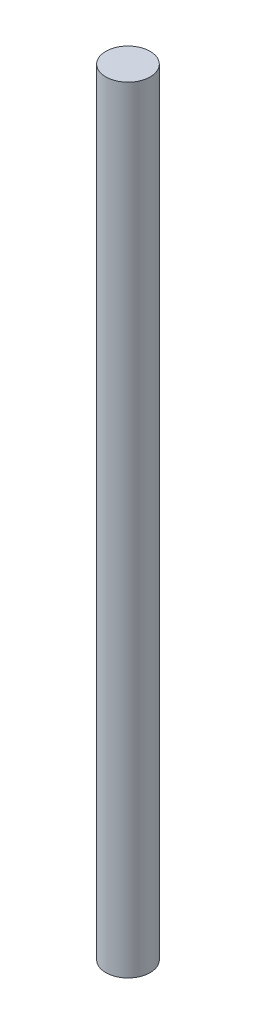
SolidWorks part; units mm, degrees
material "Brass"
ref_plane "Plan de face" through (0, 0, 0) normal (0, 0, 1) x (1, 0, 0)
ref_plane "Plan de dessus" through (0, 0, 0) normal (0, 1, 0) x (1, 0, 0)
ref_plane "Plan de droite" through (0, 0, 0) normal (1, 0, 0) x (0, 0, -1)
sketch "Sketch1" plane through (0, 0, 0) normal (0, 1, 0) x (1, 0, 0)
  circle A0 centre (0, 0) radius 1
  dimension "D1" = 2
extrude "Boss-Extrude1" add sketch "Sketch1" along normal blind 35
